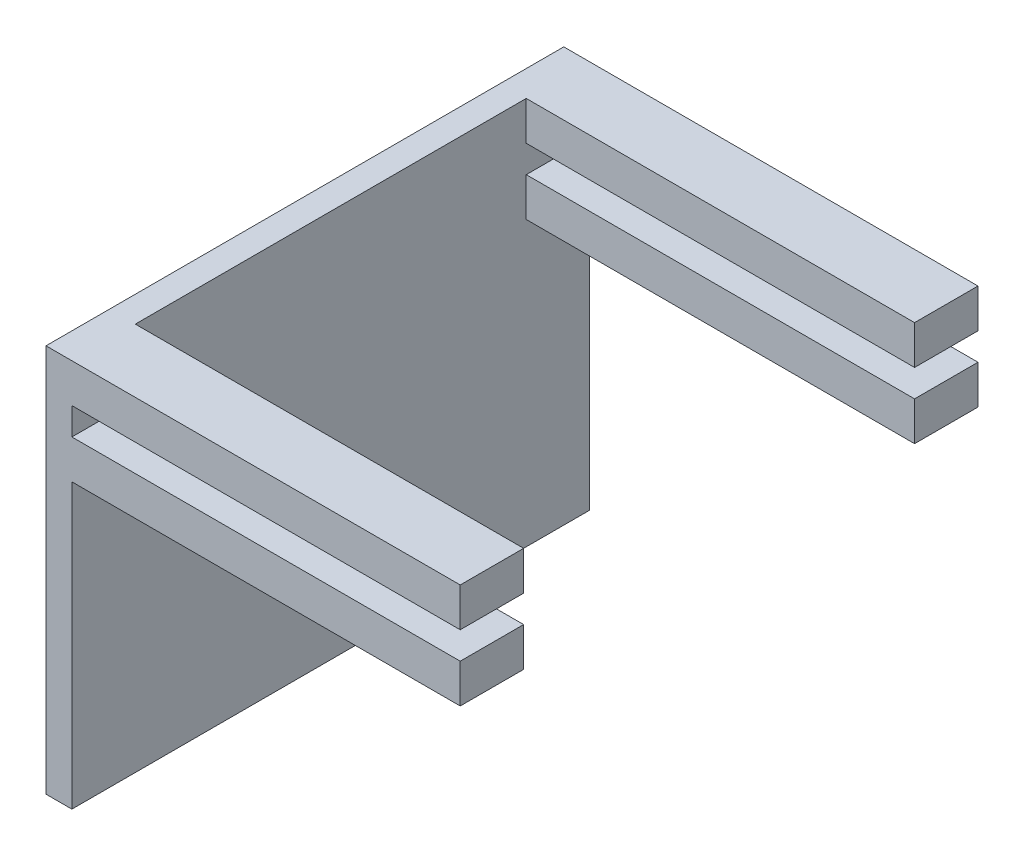
SolidWorks part; units mm, degrees
ref_plane "Přední rovina" through (0, 0, 0) normal (0, 0, 1) x (1, 0, 0)
ref_plane "Horní rovina" through (0, 0, 0) normal (0, 1, 0) x (1, 0, 0)
ref_plane "Pravá rovina" through (0, 0, 0) normal (1, 0, 0) x (0, 0, -1)
sketch "Skica1" plane through (0, 0, 0) normal (0, 0, 1) x (1, 0, 0)
  line L1 (0, 0) -> (2, 0)
  line L2 (0, 0) -> (0, 30)
  line L3 (0, 30) -> (2, 30)
  line L4 (2, 0) -> (2, 30)
  dimension "D1" = 30
  dimension "D2" = 2
extrude "Přidat vysunutím1" add sketch "Skica1" along normal blind 40
sketch "Skica2" plane through (2, 0, 0) normal (1, 0, 0) x (0, 0, -1)
  line L1 (-40, 30) -> (-35.1, 30)
  line L2 (-40, 30) -> (-40, 27)
  line L3 (-40, 27) -> (-35.1, 27)
  line L4 (-35.1, 30) -> (-35.1, 27)
  line L18 (-40, 0) -> (-40, 30) construction
  line L19 (0, 30) -> (-4.9, 30)
  line L20 (0, 30) -> (0, 27)
  line L21 (0, 27) -> (-4.9, 27)
  line L22 (-4.9, 30) -> (-4.9, 27)
  line L23 (-40, 24.9) -> (-35.1, 24.9)
  line L24 (-40, 24.9) -> (-40, 21.9)
  line L25 (-40, 21.9) -> (-35.1, 21.9)
  line L26 (-35.1, 24.9) -> (-35.1, 21.9)
  line L27 (0, 0) -> (0, 30) construction
  line L28 (0, 24.9) -> (-4.9, 24.9)
  line L29 (0, 24.9) -> (0, 21.9)
  line L30 (0, 21.9) -> (-4.9, 21.9)
  line L31 (-4.9, 24.9) -> (-4.9, 21.9)
  dimension "D1" = 4.9
  dimension "D2" = 3
  dimension "D3" = 2.1
extrude "Přidat vysunutím2" add sketch "Skica2" along normal blind 30
sketch "Skica3" plane through (0, 0, 0) normal (0, 0, -1) x (-1, 0, 0)
  line L0 (1, 14) -> (1, 4) construction
  line L1 (2, 14) -> (2, 4)
  line L2 (0, 14) -> (0, 4)
  line L3 (0, 30) -> (0, 0) construction
  line L4 (0, 0) -> (-2, 0) construction
  line L5 (4, 14) -> (4, 4)
  line L6 (-2, 14) -> (-2, 4)
  line L7 (0, 1.1716) -> (0, 16.8284)
  arc A0 (2, 14) -> (0, 14) centre (1, 14) ccw
  arc A1 (0, 4) -> (2, 4) centre (1, 4) ccw
  arc A2 (-2, 4) -> (4, 4) centre (1, 4) ccw
  arc A3 (4, 14) -> (-2, 14) centre (1, 14) ccw
  point P2 (1, 9)
  line M10 (0, 0) -> (0, 30)
  dimension "D1" = 1
  dimension "D2" = 10
  dimension "D3" = 4
  dimension "D4" = 2
extrude "Přidat vysunutím3" add sketch "Skica3" against normal blind 2 contours L5 A3 A0 L1 A1 A2 M10
